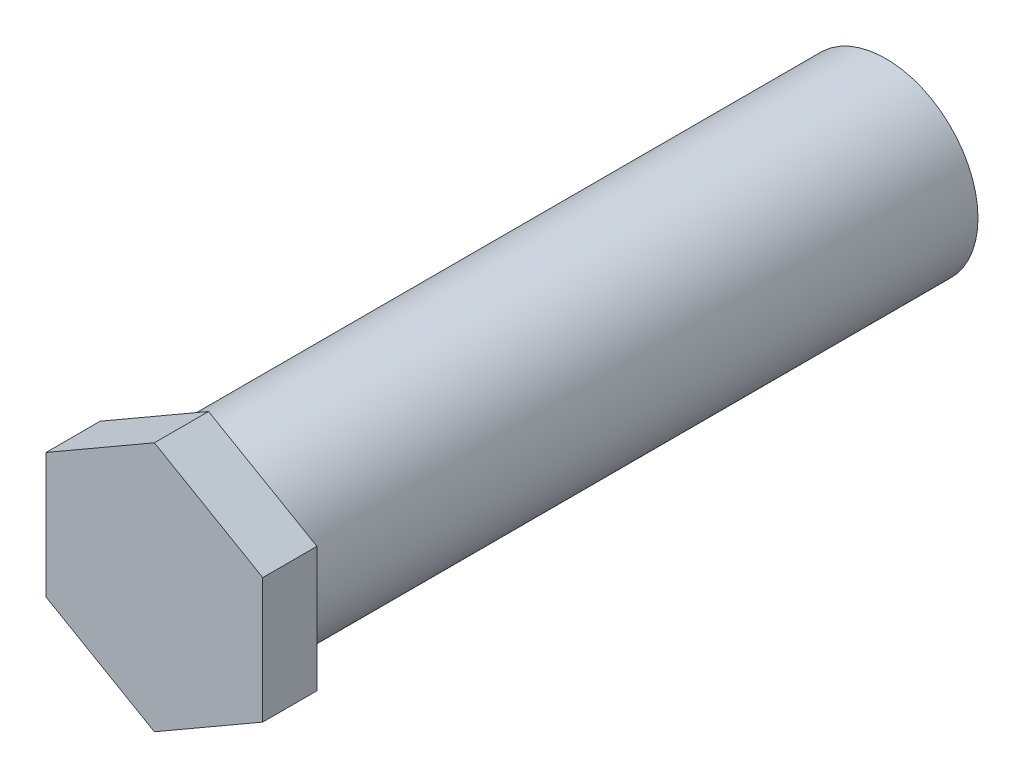
SolidWorks part; units mm, degrees
ref_plane "Front Plane" through (0, 0, 0) normal (0, 0, 1) x (1, 0, 0)
ref_plane "Top Plane" through (0, 0, 0) normal (0, 1, 0) x (1, 0, 0)
ref_plane "Right Plane" through (0, 0, 0) normal (1, 0, 0) x (0, 0, -1)
sketch "Sketch1" plane through (0, 0, 0) normal (0, 0, 1) x (1, 0, 0)
  circle A0 centre (0, 0) radius 3.4
  dimension "D1" = 6.8
extrude "Boss-Extrude1" add sketch "Sketch1" against normal blind 25
cosmetic thread "Cosmetic Thread1" parameters "D1"=19, "D2"=5.1
sketch "Sketch2" plane through (0, 0, 0) normal (0, 0, 1) x (1, 0, 0)
  line L1 (-4, -2.3094) -> (0, -4.6188)
  line L2 (0, -4.6188) -> (4, -2.3094)
  line L3 (4, -2.3094) -> (4, 2.3094)
  line L4 (4, 2.3094) -> (0, 4.6188)
  line L5 (0, 4.6188) -> (-4, 2.3094)
  line L6 (-4, 2.3094) -> (-4, -2.3094)
  circle A0 centre (0, 0) radius 4 construction
  dimension "D1" = 8
extrude "Boss-Extrude2" add sketch "Sketch2" along normal blind 2
